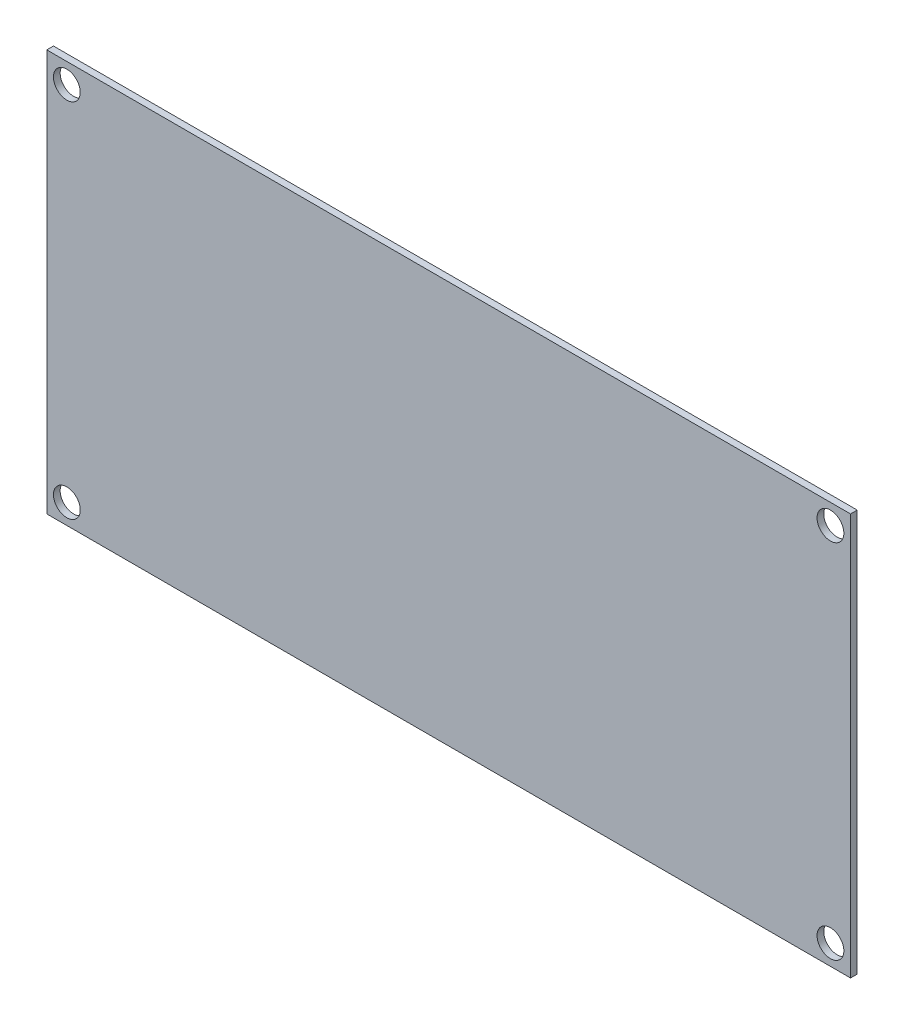
SolidWorks part; units mm, degrees
ref_plane "Front Plane" through (0, 0, 0) normal (0, 0, 1) x (1, 0, 0)
ref_plane "Top Plane" through (0, 0, 0) normal (0, 1, 0) x (1, 0, 0)
ref_plane "Right Plane" through (0, 0, 0) normal (1, 0, 0) x (0, 0, -1)
sketch "Sketch1" plane through (0, 0, 0) normal (0, 0, 1) x (1, 0, 0)
  line L1 (-38.1, -19.05) -> (38.1, -19.05)
  line L2 (-38.1, -19.05) -> (-38.1, 19.05)
  line L3 (-38.1, 19.05) -> (38.1, 19.05)
  line L4 (38.1, -19.05) -> (38.1, 19.05)
  line L5 (-38.1, -19.05) -> (38.1, 19.05) construction
  line L6 (-38.1, 19.05) -> (38.1, -19.05) construction
  point P0 (0, 0)
  dimension "D1" = 76.2
  dimension "D2" = 38.1
extrude "Boss-Extrude1" add sketch "Sketch1" along normal blind 0.635 contours L3 L4 L1 L2
sketch "Sketch2" plane through (0, 0, 0.635) normal (0, 0, 1) x (1, 0, 0)
  line L0 (-36.195, 17.145) -> (-36.195, 19.05) construction
  line L1 (-38.1, 19.05) -> (38.1, 19.05) construction
  line L2 (-36.195, -17.145) -> (-36.195, -19.05)
  line L4 (-38.1, -19.05) -> (38.1, -19.05) construction
  line L6 (-36.195, -17.145) -> (-38.1, -17.145) construction
  line L10 (-38.1, -19.05) -> (-38.1, 19.05) construction
  line L14 (-36.195, 17.145) -> (-38.1, 17.145) construction
  line L18 (36.195, 17.145) -> (36.195, 19.05) construction
  line L19 (36.195, 17.145) -> (38.1, 17.145) construction
  line L20 (38.1, -19.05) -> (38.1, 19.05) construction
  line L24 (36.195, -17.145) -> (38.1, -17.145) construction
  line L25 (36.195, -17.145) -> (36.195, -19.05) construction
  circle A4 centre (-36.195, 17.145) radius 1.27
  circle A5 centre (-36.195, -17.145) radius 1.27
  circle A6 centre (36.195, -17.145) radius 1.27
  circle A7 centre (36.195, 17.145) radius 1.27
  point P0 (-36.195, 17.145)
  point P1 (36.195, 17.145)
  point P2 (36.195, -17.145)
  point P3 (-36.195, -17.145)
  dimension "D1" = 1.905
  dimension "D2" = 2.54
extrude "Cut-Extrude4" cut sketch "Sketch2" against normal through all contours A4 | A5 | A6 | A7
